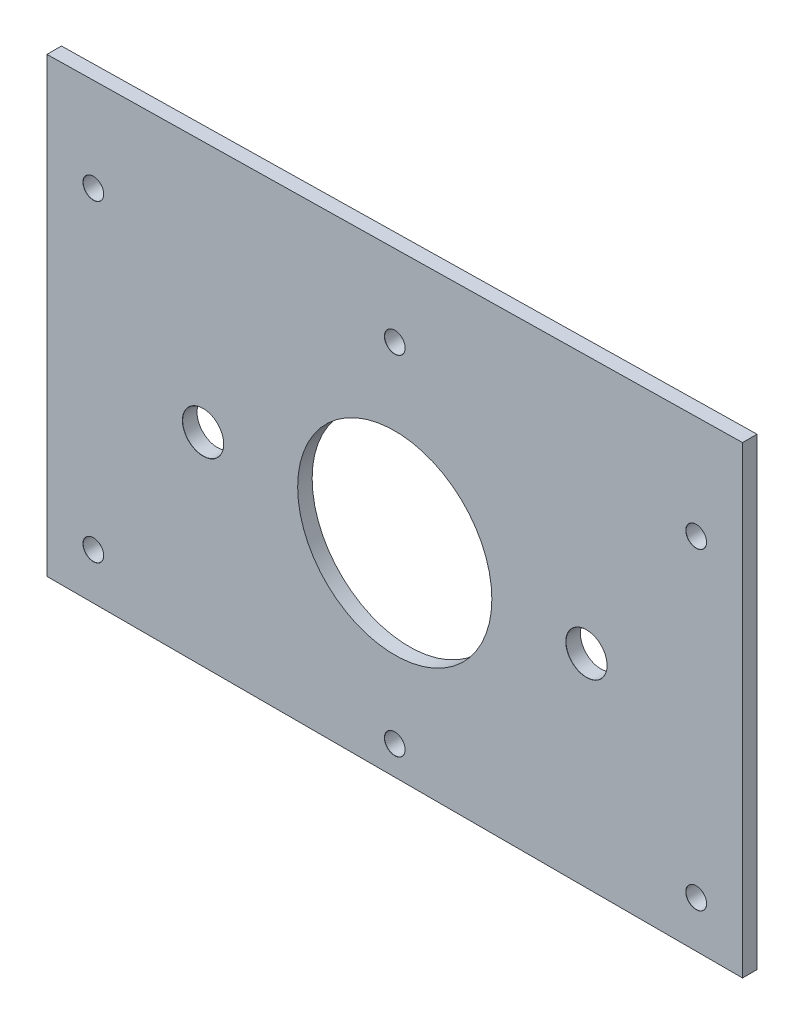
SolidWorks part; units mm, degrees
material "Alloy Steel (SS)"
ref_plane "X-Y Datum" through (0, 0, 0) normal (0, 0, 1) x (1, 0, 0)
ref_plane "X-Z Datum" through (0, 0, 0) normal (0, 1, 0) x (1, 0, 0)
ref_plane "Y-Z Datum" through (0, 0, 0) normal (1, 0, 0) x (0, 0, -1)
sketch "Sketch1" plane through (0, 0, 0) normal (0, 0, 1) x (1, 0, 0)
  line L0 (-76.2, 54.61) -> (-76.2, 44.45)
  line L1 (-76.2, 44.45) -> (76.2, 44.45) construction
  line L2 (-76.2, 44.45) -> (-76.2, -44.45)
  line L3 (-76.2, -44.45) -> (76.2, -44.45)
  line L4 (76.2, 44.45) -> (76.2, -44.45)
  line L5 (-76.2, 44.45) -> (76.2, -44.45) construction
  line L6 (-76.2, -44.45) -> (76.2, 44.45) construction
  line L7 (76.2, 44.45) -> (76.2, 57.15)
  line L10 (-76.2, 54.61) -> (76.2, 57.15)
  point P0 (0, 0)
  dimension "D1" = 152.4
  dimension "D2" = 88.9
  dimension "D3" = 12.7
  dimension "D4" = 10.16
extrude "Boss-Extrude1" add sketch "Sketch1" along normal blind 3.175
hole_wizard "M4 Clearance Hole1" positions "Sketch7" profile "Sketch8" hole size "M4" standard "ANSI Metric" end condition through all
sketch "Sketch7" plane through (0, 0, 3.175) normal (0, 0, 1) x (1, 0, 0)
  line L0 (-75.8701, 0) -> (49924.1299, 0) construction
  line L1 (0, 56.7764) -> (0, -49943.2236) construction
  line L2 (-76.2, -44.45) -> (76.2, -44.45) construction
  line L10 (-76.2, 0) -> (76.2, 0) construction
  line L11 (-76.2, 54.61) -> (-76.2, -44.45) construction
  line L12 (76.2, -44.45) -> (76.2, 57.15) construction
  line L14 (-69.85, -44.45) -> (-69.85, 54.7158) construction
  line L15 (-76.2, -44.45) -> (76.2, -44.45) construction
  line L16 (76.2, 57.15) -> (-76.2, 54.61) construction
  line L17 (69.85, -44.45) -> (69.85, 57.0442) construction
  line L18 (66.04, -44.45) -> (66.04, 56.9807) construction
  line L20 (-66.04, -44.45) -> (-66.04, 54.7793) construction
  line L21 (-76.2, -38.1) -> (76.2, -38.1) construction
  line L22 (-76.2, 34.29) -> (76.2, 34.29) construction
  line L23 (-76.2, -34.29) -> (76.2, -34.29) construction
  line L24 (-76.2, 38.1) -> (76.2, 38.1) construction
  circle A10 centre (-66.04, 34.29) radius 6.35
  circle A11 centre (-66.04, -34.29) radius 6.35
  circle A12 centre (0, -38.1) radius 6.35
  circle A13 centre (66.04, -34.29) radius 6.35
  circle A14 centre (66.04, 34.29) radius 6.35
  circle A15 centre (0, 38.1) radius 6.35
  circle A16 centre (-69.85, 0) radius 6.35
  circle A17 centre (69.85, 0) radius 6.35
  point P174 (-66.04, 34.29)
  point P176 (-66.04, -34.29)
  point P178 (0, -38.1)
  point P180 (66.04, -34.29)
  point P182 (66.04, 34.29)
  point P184 (0, 38.1)
  dimension "D1" = 6.35
  dimension "D9" = 12.7
  dimension "D2" = 146.05
  dimension "D3" = 142.24
  dimension "D4" = 6.35
  dimension "D5" = 10.16
  dimension "D6" = 10.16
  dimension "D7" = 78.74
  dimension "D8" = 82.55
sketch "Sketch8" plane through (0, 38.1, 3.175) normal (1, 0, 0) x (0, -1, 0)
  line L0 (0, 0) -> (0, 3.175)
  line L1 (0, 3.175) -> (2.25, 3.175)
  line L2 (2.25, 3.175) -> (2.25, 0.025)
  line L3 (2.25, 0.025) -> (2.275, 0)
  line L5 (2.275, 0) -> (0, 0)
  line L6 (-2.25, 0.025) -> (-2.275, 0) construction
  line L11 (0, -6.35) -> (0, 107.95) construction
  dimension "Thru Hole Dia." = 4.5
  dimension "Thru Hole Depth" = 3.175
  dimension "Near C'Sink Dia." = 4.55
  dimension "Near C'Sink Angle" = 90
sketch "Sketch9" plane through (0, 0, 3.175) normal (0, 0, 1) x (1, 0, 0)
  line L0 (-42, 0) -> (42, 0) construction
  line L1 (0, -44.45) -> (0, 42.6782) construction
  line L2 (-76.2, -44.45) -> (76.2, -44.45) construction
  circle A0 centre (0, 0) radius 21.275
  circle A1 centre (42, 0) radius 4 construction
  circle A2 centre (-42, 0) radius 4 construction
  dimension "D1" = 42.55
  dimension "D3" = 8
  dimension "D2" = 42
hole_wizard "M8 Clearance Hole1" positions "Sketch10" profile "Sketch11" hole size "M8" standard "ANSI Metric" end condition through all
sketch "Sketch10" plane through (0, 0, 3.175) normal (0, 0, 1) x (1, 0, 0)
  point P0 (-42, 0)
  point P3 (42, 0)
sketch "Sketch11" plane through (-42, 0, 3.175) normal (1, 0, 0) x (0, -1, 0)
  line L0 (0, 0) -> (0, 3.175)
  line L1 (0, 3.175) -> (4.5, 3.175)
  line L2 (4.5, 3.175) -> (4.5, 0.025)
  line L3 (4.5, 0.025) -> (4.525, 0)
  line L5 (4.525, 0) -> (0, 0)
  line L6 (-4.5, 0.025) -> (-4.525, 0) construction
  line L11 (0, -6.35) -> (0, 107.95) construction
  dimension "Thru Hole Dia." = 9
  dimension "Thru Hole Depth" = 3.175
  dimension "Near C'Sink Dia." = 9.05
  dimension "Near C'Sink Angle" = 90
extrude "Center Hole" cut sketch "Sketch9" against normal through all
